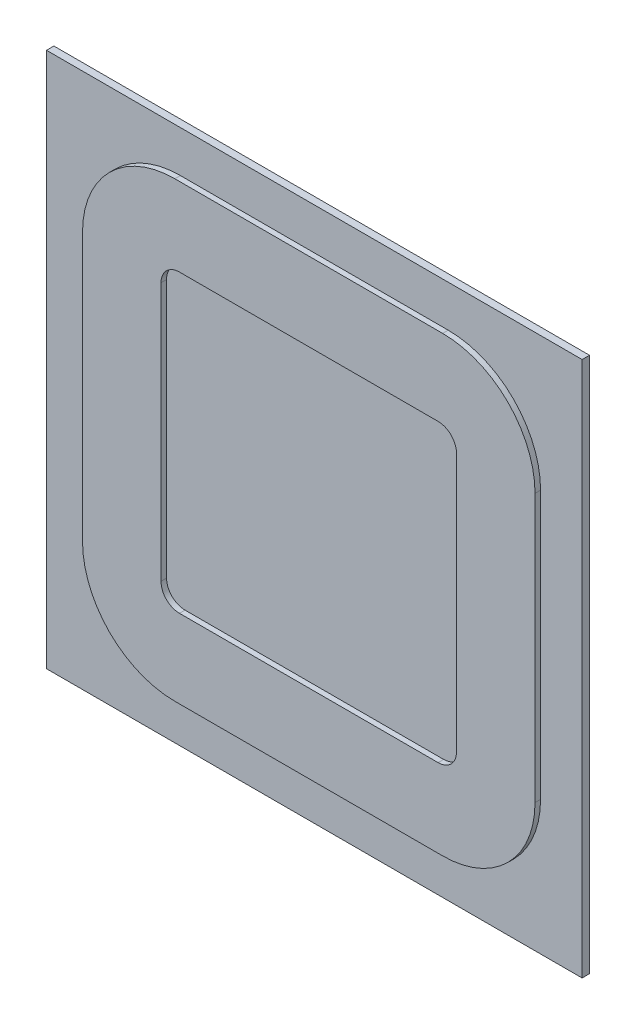
SolidWorks part; units mm, degrees
ref_plane "Front Plane" through (0, 0, 0) normal (0, 0, 1) x (1, 0, 0)
ref_plane "Top Plane" through (0, 0, 0) normal (0, 1, 0) x (1, 0, 0)
ref_plane "Right Plane" through (0, 0, 0) normal (1, 0, 0) x (0, 0, -1)
sketch "Sketch1" plane through (0, 0, 0) normal (0, 0, 1) x (1, 0, 0)
  line L1 (0, 0) -> (29, 0)
  line L2 (0, 0) -> (0, 29)
  line L3 (0, 29) -> (29, 29)
  line L4 (29, 0) -> (29, 29)
  dimension "D1" = 29
  dimension "D2" = 29
extrude "Boss-Extrude1" add sketch "Sketch1" along normal blind 0.4
sketch "Sketch2" plane through (0, 0, 0.4) normal (0, 0, 1) x (1, 0, 0)
  line L0 (0, 0) -> (29, 0) construction
  line L1 (2.25, 26.75) -> (26.75, 26.75)
  line L2 (2.25, 26.75) -> (2.25, 2.25)
  line L3 (2.25, 2.25) -> (26.75, 2.25)
  line L4 (26.75, 26.75) -> (26.75, 2.25)
  line L5 (6.5, 22.5) -> (22.5, 22.5)
  line L6 (6.5, 22.5) -> (6.5, 6.5)
  line L7 (6.5, 6.5) -> (22.5, 6.5)
  line L8 (22.5, 22.5) -> (22.5, 6.5)
  line L9 (0, 29) -> (0, 0) construction
  dimension "D1" = 24.5
  dimension "D2" = 24.5
  dimension "D3" = 16
  dimension "D4" = 16
  dimension "D5" = 2.25
  dimension "D6" = 2.25
  dimension "D7" = 6.5
  dimension "D8" = 6.5
extrude "Boss-Extrude2" add sketch "Sketch2" along normal blind 0.3
fillet "Fillet1" radius 5 4 edges at (2.25, 2.25, 0.55) (26.75, 2.25, 0.55) (26.75, 26.75, 0.55) (2.25, 26.75, 0.55)
fillet "Fillet2" radius 1 4 edges at (6.5, 22.5, 0.55) (22.5, 22.5, 0.55) (22.5, 6.5, 0.55) (6.5, 6.5, 0.55)
